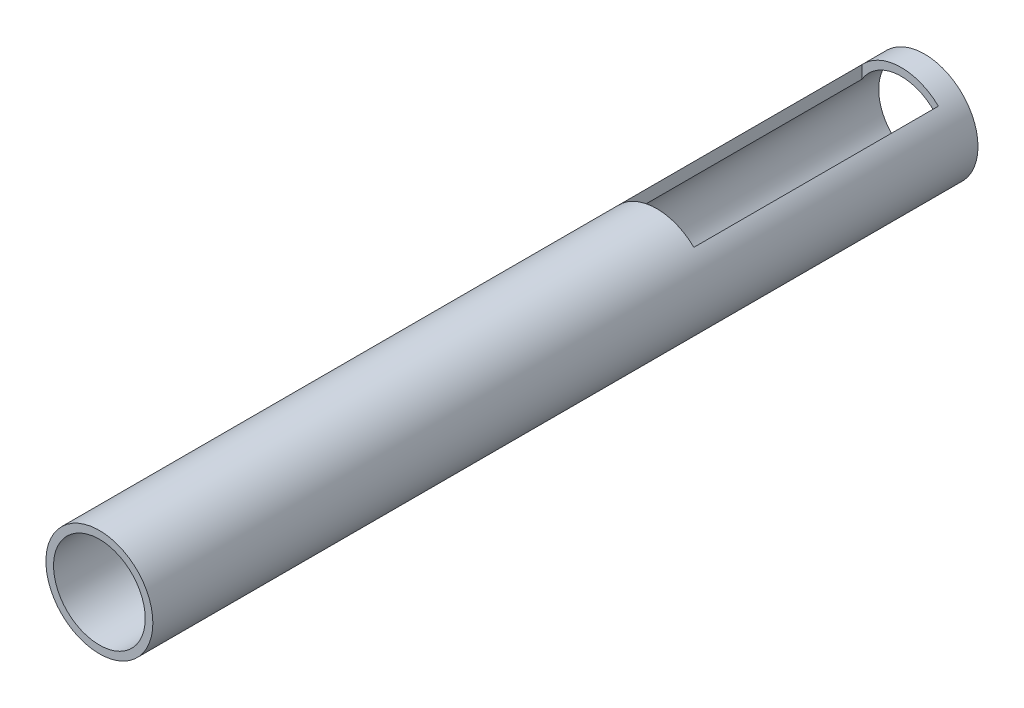
SolidWorks part; units mm, degrees
ref_plane "Front Plane" through (0, 0, 0) normal (0, 0, 1) x (1, 0, 0)
ref_plane "Top Plane" through (0, 0, 0) normal (0, 1, 0) x (1, 0, 0)
ref_plane "Right Plane" through (0, 0, 0) normal (1, 0, 0) x (0, 0, -1)
sketch "Sketch3" plane through (0, 0, 0) normal (0, 0, 1) x (1, 0, 0)
  circle A0 centre (0, 0) radius 44.45
  circle A1 centre (0, 0) radius 38.1
  dimension "D1" = 88.9
  dimension "D2" = 76.2
extrude "Boss-Extrude3" add sketch "Sketch3" along normal blind 685.8
sketch "Sketch4" plane through (0, 0, 0) normal (0, 1, 0) x (1, 0, 0)
  line L1 (-32.6424, -19.3531) -> (30.8576, -19.3531)
  line L2 (-32.6424, -19.3531) -> (-32.6424, -222.5531)
  line L3 (-32.6424, -222.5531) -> (30.8576, -222.5531)
  line L4 (30.8576, -19.3531) -> (30.8576, -222.5531)
  dimension "D1" = 63.5
  dimension "D2" = 203.2
extrude "Cut-Extrude2" cut sketch "Sketch4" along normal blind 685.8
